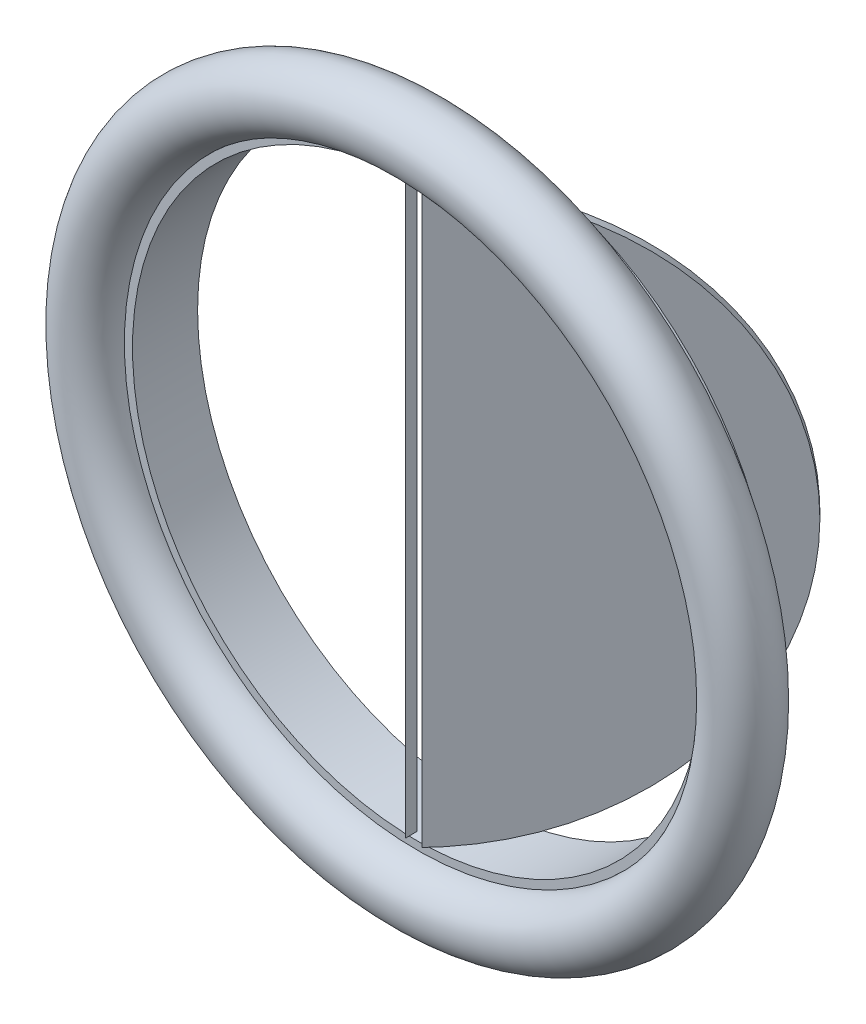
SolidWorks part; units mm, degrees
ref_plane "Front Plane" through (0, 0, 0) normal (0, 0, 1) x (1, 0, 0)
ref_plane "Top Plane" through (0, 0, 0) normal (0, 1, 0) x (1, 0, 0)
ref_plane "Right Plane" through (0, 0, 0) normal (1, 0, 0) x (0, 0, -1)
sketch "Sketch1" plane through (0, 0, 0) normal (1, 0, 0) x (0, 0, -1)
  circle A0 centre (0, 0) radius 1
  dimension "D1" = 2
sketch "Sketch2" plane through (0, 0, 0) normal (1, 0, 0) x (0, 0, -1)
  line L0 (-4.0625, 10) -> (11.6875, 10) construction
  dimension "D1" = 10
revolve "Revolve1" add sketch "Sketch1" angle 360 about L0
sketch "Sketch3" plane through (0, 0, 0) normal (1, 0, 0) x (0, 0, -1)
  line L0 (0, 22.9629) -> (0, -2.9629) construction
ref_plane "Plane1" through (0, 0, 0) normal (0.7071, 0, 0.7071) x (0, -1, 0)
ref_plane "Plane2" through (0, 0, 0) normal (0.7071, 0, -0.7071) x (0, -1, 0)
sketch "Sketch4" plane through (0, 0, 0) normal (0.7071, 0, -0.7071) x (0, -1, 0)
  line L0 (-18.75, 0) -> (-1.25, 0)
  line L1 (-22.9629, 0) -> (2.9629, 0) construction
  arc A0 (-1.25, 0) -> (-18.75, 0) centre (-10, 0) ccw
  dimension "D1" = 17.5
  dimension "D2" = 18.75
extrude "Boss-Extrude1" add sketch "Sketch4" against normal blind 0.25 separate body
sketch "Sketch5" plane through (0, 0, 0) normal (0.7071, 0, 0.7071) x (0, -1, 0)
  line L0 (-18.75, -0.25) -> (-1.25, -0.25)
sketch "Sketch9" plane through (0, 0, 0) normal (0.7071, 0, 0.7071) x (0, -1, 0)
  line L0 (-1.25, 0) -> (-18.75, 0)
  arc A0 (-18.75, 0) -> (-1.25, 0) centre (-10, 0) cw
extrude "Boss-Extrude5" add sketch "Sketch9" along normal blind 0.25 separate body
sketch "Sketch10" plane through (0, 0, 0) normal (0, 0, 1) x (1, 0, 0)
  line L0 (0, 22.9629) -> (0, -2.9629) construction
  line L1 (0.25, 18.9965) -> (-0.25, 18.9965)
  line L2 (0.25, 18.9965) -> (0.25, 1.0035)
  line L3 (0.25, 1.0035) -> (-0.25, 1.0035)
  line L4 (-0.25, 18.9965) -> (-0.25, 1.0035)
  line L5 (0.25, 18.9965) -> (-0.25, 1.0035) construction
  line L6 (0.25, 1.0035) -> (-0.25, 18.9965) construction
  circle A0 centre (0, 10) radius 9 construction
  point P0 (0, 10)
  dimension "D1" = 0.5
extrude "Cut-Extrude2" cut sketch "Sketch10" against normal through all both and the other way through all
sketch "Sketch11" plane through (0, 0, 0) normal (0, 0, 1) x (1, 0, 0)
  line L0 (0, 22.9629) -> (0, -2.9629) construction
  circle A0 centre (0, 10) radius 9
  circle A1 centre (0, 10) radius 8.75
  dimension "D1" = 0.25
  dimension "D2" = 18
extrude "Boss-Extrude6" add sketch "Sketch11" against normal blind 2
